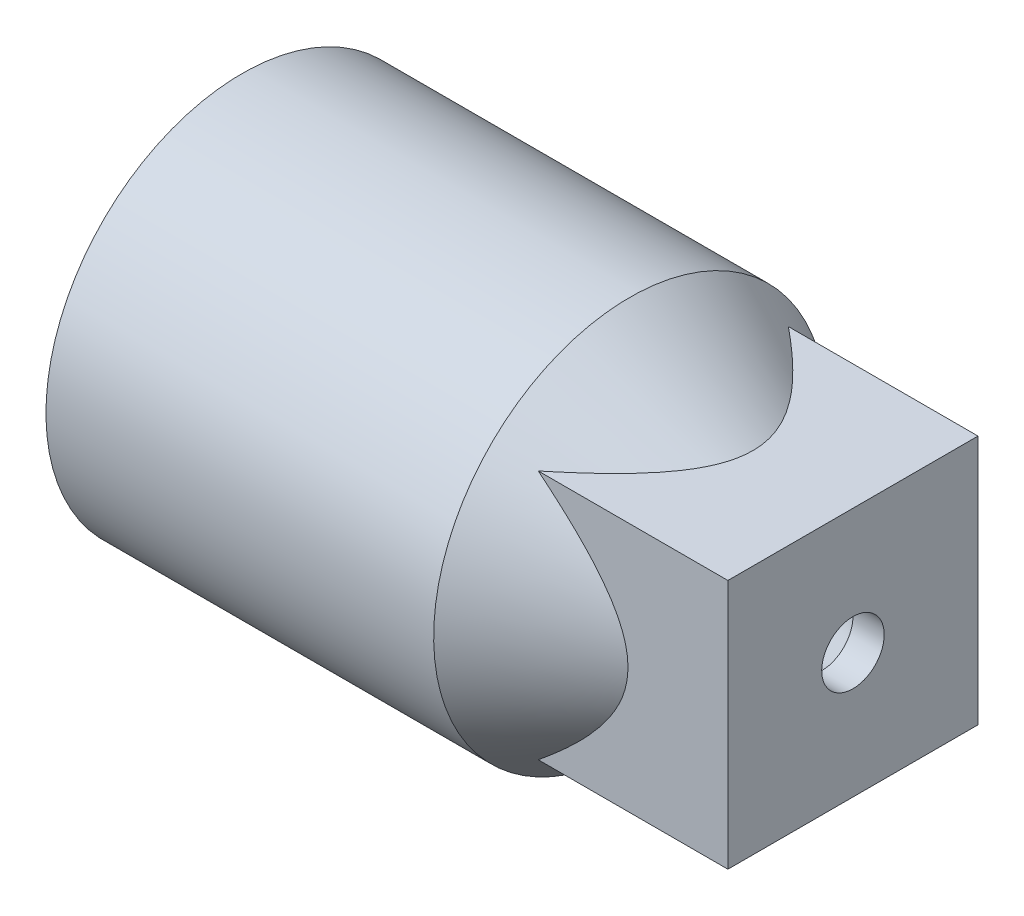
SolidWorks part; units mm, degrees
ref_plane "Alzado" through (0, 0, 0) normal (0, 0, 1) x (1, 0, 0)
ref_plane "Planta" through (0, 0, 0) normal (0, 1, 0) x (1, 0, 0)
ref_plane "Vista lateral" through (0, 0, 0) normal (1, 0, 0) x (0, 0, -1)
sketch "Croquis1" plane through (0, 0, 0) normal (0, 0, 1) x (1, 0, 0)
  line L0 (37.077, 2) -> (37.077, 0) construction
  line L1 (0, 9.55) -> (24, 9.55)
  line L2 (24, 9.55) -> (37.077, 2)
  line L3 (0, 9.55) -> (0, 0) construction
  line L4 (0, 0) -> (37.077, 0) construction
  line L5 (0, 12.55) -> (24.8038, 12.55)
  line L6 (24.8038, 12.55) -> (37.077, 5.4641)
  line L7 (0, 12.55) -> (0, 9.55)
  line L8 (37.077, 2) -> (37.077, 5.4641)
  line L9 (24.8038, 12.55) -> (38.577, 4.5981) construction
  dimension "D1" = 9.55
  dimension "D2" = 2
  dimension "D3" = 24
  dimension "D4" = 30
  dimension "D5" = 3
revolve "Revolución1" add sketch "Croquis1" angle 360 about L4
chamfer "Chaflán1" distance 1.5 angle 45 1 edges at (0, -9.55, 0)
sketch "Croquis3" plane through (37.077, 0, 0) normal (1, 0, 0) x (0, 0, -1)
  line L1 (-8, -8) -> (8, -8)
  line L2 (-8, -8) -> (-8, 8)
  line L3 (-8, 8) -> (8, 8)
  line L4 (8, -8) -> (8, 8)
  line L5 (-8, -8) -> (8, 8) construction
  line L6 (-8, 8) -> (8, -8) construction
  circle A0 centre (0, 0) radius 2 construction
  circle A1 centre (0, 0) radius 2
  point P0 (0, 0)
  dimension "D1" = 16
extrude "Saliente-Extruir1" add sketch "Croquis3" along normal blind 2 and the other way up to next
